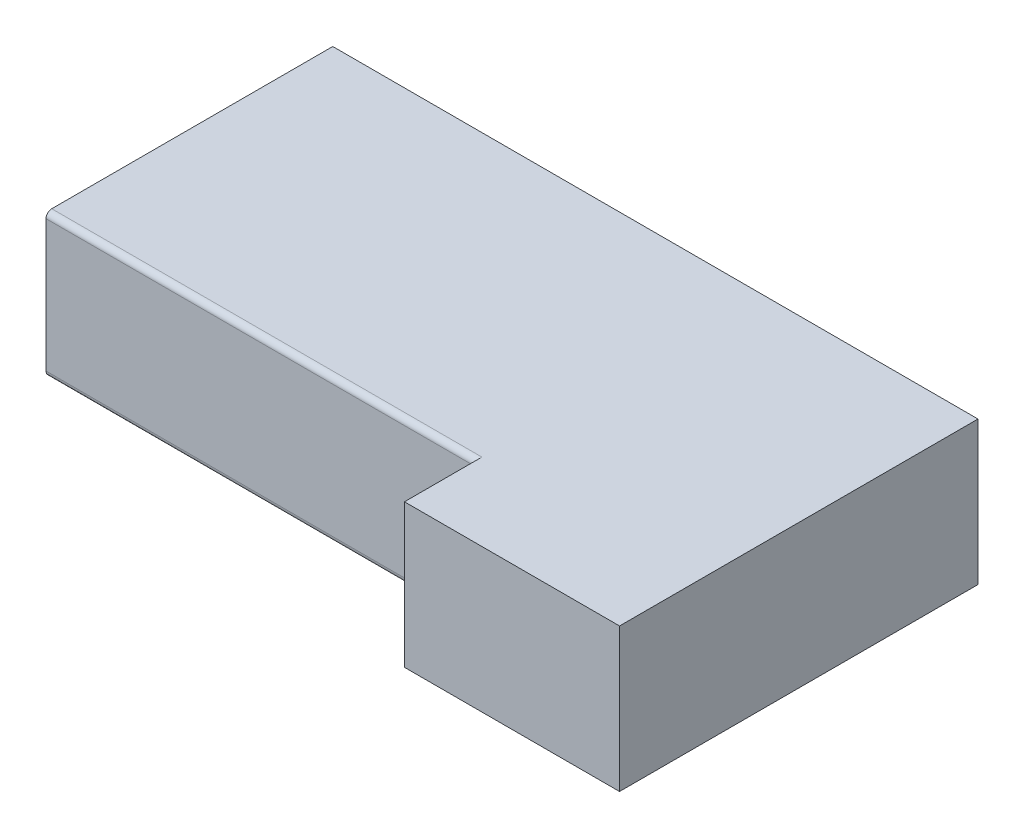
SolidWorks part; units mm, degrees
ref_plane "Front Plane" through (0, 0, 0) normal (0, 0, 1) x (1, 0, 0)
ref_plane "Top Plane" through (0, 0, 0) normal (0, 1, 0) x (1, 0, 0)
ref_plane "Right Plane" through (0, 0, 0) normal (1, 0, 0) x (0, 0, -1)
sketch "Sketch1" plane through (0, 0, 0) normal (0, 1, 0) x (1, 0, 0)
  line L1 (-28.575, 12.7) -> (28.575, 12.7)
  line L2 (-28.575, 12.7) -> (-28.575, -12.7)
  line L3 (-28.575, -12.7) -> (28.575, -12.7)
  line L4 (28.575, 12.7) -> (28.575, -12.7)
  line L5 (-28.575, 12.7) -> (28.575, -12.7) construction
  line L6 (-28.575, -12.7) -> (28.575, 12.7) construction
  point P0 (0, 0)
  dimension "D1" = 57.15
  dimension "D2" = 25.4
extrude "Boss-Extrude1" add sketch "Sketch1" along normal mid plane 12.7
sketch "Sketch2" plane through (0, 0, 12.7) normal (0, 0, 1) x (1, 0, 0)
  line L0 (-28.575, -6.35) -> (28.575, -6.35) construction
  line L1 (28.575, 6.35) -> (9.525, 6.35)
  line L2 (28.575, 6.35) -> (28.575, -6.35)
  line L3 (28.575, -6.35) -> (9.525, -6.35)
  line L4 (9.525, 6.35) -> (9.525, -6.35)
  dimension "D1" = 19.05
extrude "Boss-Extrude2" add sketch "Sketch2" along normal blind 6.35
fillet "Fillet1" radius 0.508 2 edges at (-9.525, -6.35, 12.7) (-9.525, 6.35, 12.7)
